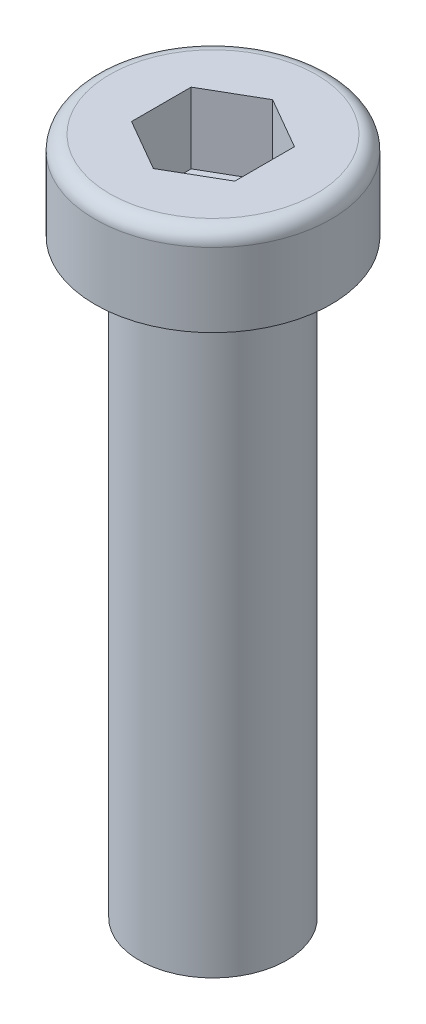
SolidWorks part; units mm, degrees
ref_plane "Front Plane" through (0, 0, 0) normal (0, 0, 1) x (1, 0, 0)
ref_plane "Top Plane" through (0, 0, 0) normal (0, 1, 0) x (1, 0, 0)
ref_plane "Right Plane" through (0, 0, 0) normal (1, 0, 0) x (0, 0, -1)
sketch "Sketch1" plane through (0, 0, 0) normal (0, 0, 1) x (1, 0, 0)
  line L0 (0, 46) -> (-7, 46)
  line L1 (-8, 45) -> (-8, 40)
  line L2 (-8, 40) -> (-5, 40)
  line L3 (-5, 40) -> (-5, 0)
  line L4 (-5, 0) -> (0, 0)
  line L5 (0, 0) -> (0, 46)
  arc A0 (-7, 46) -> (-8, 45) centre (-7, 45) ccw
  dimension "D5" = 1
  dimension "D1" = 6
  dimension "D2" = 8
  dimension "D3" = 40
  dimension "D4" = 5
revolve "Revolve1" add sketch "Sketch1" angle 360 about L5
sketch "Sketch2" plane through (0, 46, 0) normal (0, 1, 0) x (1, 0, 0)
  line L1 (0, 4.0415) -> (-3.5, 2.0207)
  line L2 (-3.5, 2.0207) -> (-3.5, -2.0207)
  line L3 (-3.5, -2.0207) -> (0, -4.0415)
  line L4 (0, -4.0415) -> (3.5, -2.0207)
  line L5 (3.5, -2.0207) -> (3.5, 2.0207)
  line L6 (3.5, 2.0207) -> (0, 4.0415)
  circle A0 centre (0, 0) radius 4.5
  circle A1 centre (0, 0) radius 3.5 construction
  dimension "D1" = 9
  dimension "D2" = 7
extrude "Cut-Extrude1" cut sketch "Sketch2" against normal blind 4.8 contours L1 L2 L3 L4 L5 L6
